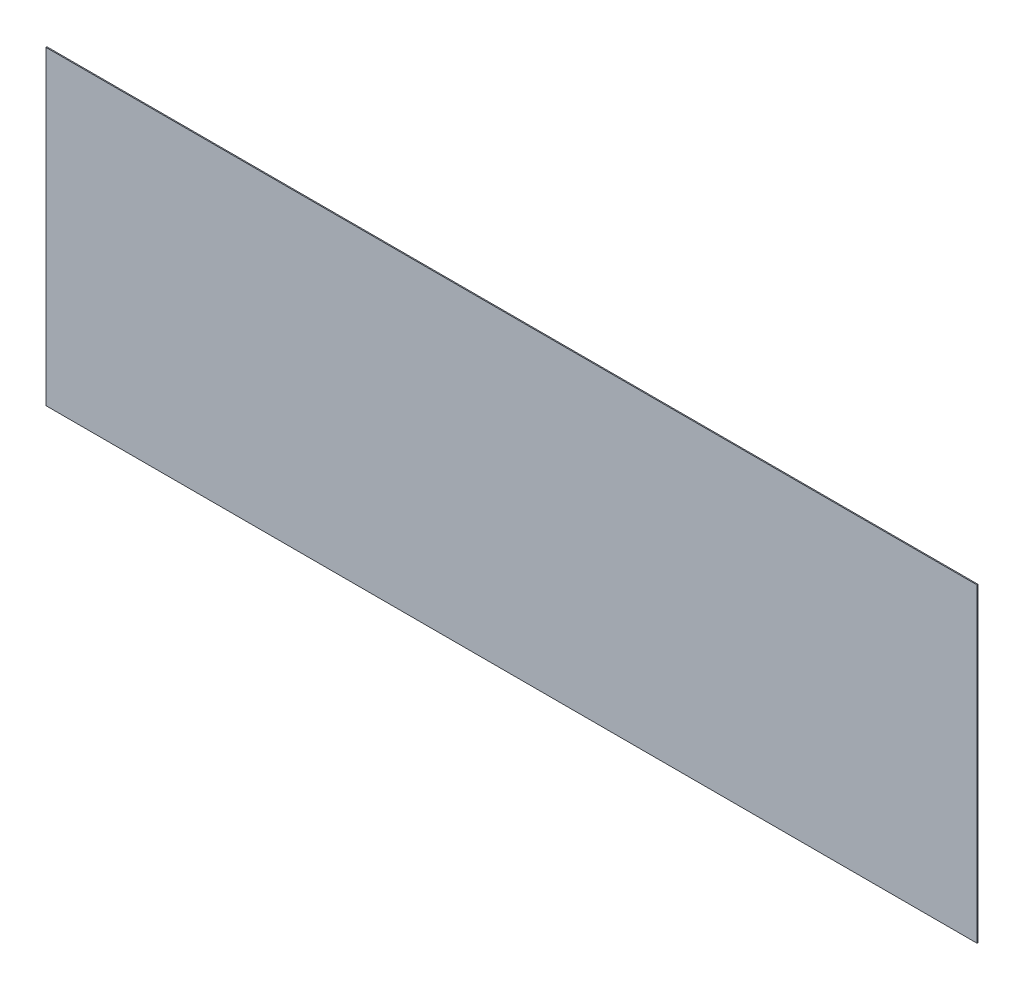
SolidWorks part; units mm, degrees
ref_plane "Front Plane" through (0, 0, 0) normal (0, 0, 1) x (1, 0, 0)
ref_plane "Top Plane" through (0, 0, 0) normal (0, 1, 0) x (1, 0, 0)
ref_plane "Right Plane" through (0, 0, 0) normal (1, 0, 0) x (0, 0, -1)
sketch "Sketch1" plane through (0, 0, 0) normal (0, 0, 1) x (1, 0, 0)
  line L0 (-237, -396.7327) -> (213, -396.7327) construction
  line L1 (213, -246.7327) -> (213, -396.7327) construction
  line L2 (-237, -246.7327) -> (213, -246.7327) construction
  line L3 (-237, -246.7327) -> (-237, -396.7327) construction
  line L4 (-237, -396.7327) -> (213, -396.7327)
  line L5 (213, -246.7327) -> (213, -396.7327)
  line L6 (-237, -246.7327) -> (213, -246.7327)
  line L7 (-237, -246.7327) -> (-237, -396.7327)
extrude "Boss-Extrude1" add sketch "Sketch1" along normal blind 0.5
